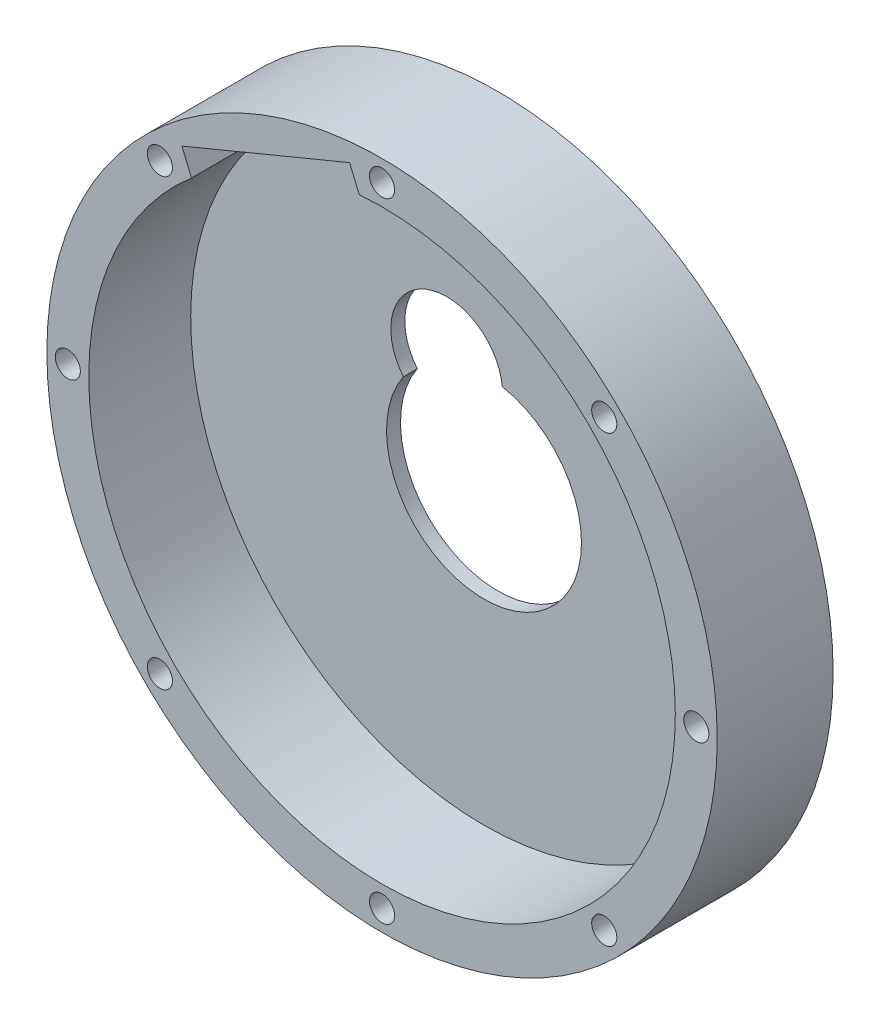
SolidWorks part; units mm, degrees
ref_plane "Plan de face" through (0, 0, 0) normal (0, 0, 1) x (1, 0, 0)
ref_plane "Plan de dessus" through (0, 0, 0) normal (0, 1, 0) x (1, 0, 0)
ref_plane "Plan de droite" through (0, 0, 0) normal (1, 0, 0) x (0, 0, -1)
sketch "Esquisse1" plane through (0, 0, 0) normal (0, 0, 1) x (1, 0, 0)
  circle A0 centre (0, 0) radius 21
  circle A1 centre (0, 0) radius 24
  circle A2 centre (0, 0) radius 22.5 construction
  circle A3 centre (22.5, 0) radius 0.9
  circle A4 centre (15.9099, -15.9099) radius 0.9
  circle A5 centre (0, -22.5) radius 0.9
  circle A6 centre (-15.9099, -15.9099) radius 0.9
  circle A7 centre (-22.5, 0) radius 0.9
  circle A8 centre (-15.9099, 15.9099) radius 0.9
  circle A9 centre (0, 22.5) radius 0.9
  circle A10 centre (15.9099, 15.9099) radius 0.9
  point P24 (0, 0)
  dimension "D1" = 8
  dimension "D2" = 42
  dimension "D3" = 45
  dimension "D4" = 48
extrude "Boss.-Extru.1" add sketch "Esquisse1" along normal blind 8.3
sketch "Esquisse2" plane through (0, 0, 0) normal (0, 0, 1) x (1, 0, 0)
  circle A0 centre (0, 0) radius 21
  dimension "D1" = 42
extrude "Boss.-Extru.2" add sketch "Esquisse2" along normal blind 1
sketch "Esquisse5" plane through (0, 0, 0) normal (0, 0, -1) x (-1, 0, 0)
  line L0 (0, 0) -> (-22.5, 0) construction
  line L1 (-18.4227, -28.7975) -> (6.8688, 32.2615) construction
  line L2 (-14.436, -19.1729) -> (-42.3383, -86.5349) construction
  line L3 (0, 0) -> (-6.2493, -15.0871) construction
  line L4 (0, 0) -> (9.1844, 22.1731) construction
  arc A0 (-1.3082, 6.8559) -> (5.7729, 3.9228) centre (0, 0) ccw
  circle A1 centre (0, 0) radius 24 construction
  arc A2 (5.7729, 3.9228) -> (-1.3082, 6.8559) centre (2.671, 6.4483) ccw
extrude "Enlèv. mat.-Extru.1" cut sketch "Esquisse5" against normal through all
sketch "Esquisse6" plane through (0, 0, 1) normal (0, 0, 1) x (1, 0, 0)
  line L0 (0, 0) -> (-4.2017, 10.1438) construction
  line L1 (-4.2017, 10.1438) -> (-8.0364, 19.4015) construction
  line L2 (-8.0364, 19.4015) -> (-9.1844, 22.1731) construction
  line L3 (-8.3226, 20.0925) -> (-14.3278, 17.6051) construction
  line L4 (-2.3174, 22.5799) -> (-14.3278, 17.6051)
  line L5 (-14.3278, 17.6051) -> (-11.2373, 10.1438)
  line L6 (-11.2373, 10.1438) -> (0.7732, 15.1187)
  line L7 (-2.3174, 22.5799) -> (0.7732, 15.1187)
  arc A0 (1.3082, 6.8559) -> (-5.7729, 3.9228) centre (-2.671, 6.4483) ccw construction
  circle A1 centre (0, 0) radius 21 construction
  circle A2 centre (0, 0) radius 24 construction
  point P17 (-5.232, 12.6313)
  dimension "D1" = 6.5
extrude "Enlèv. mat.-Extru.2" cut sketch "Esquisse6" along normal through all
